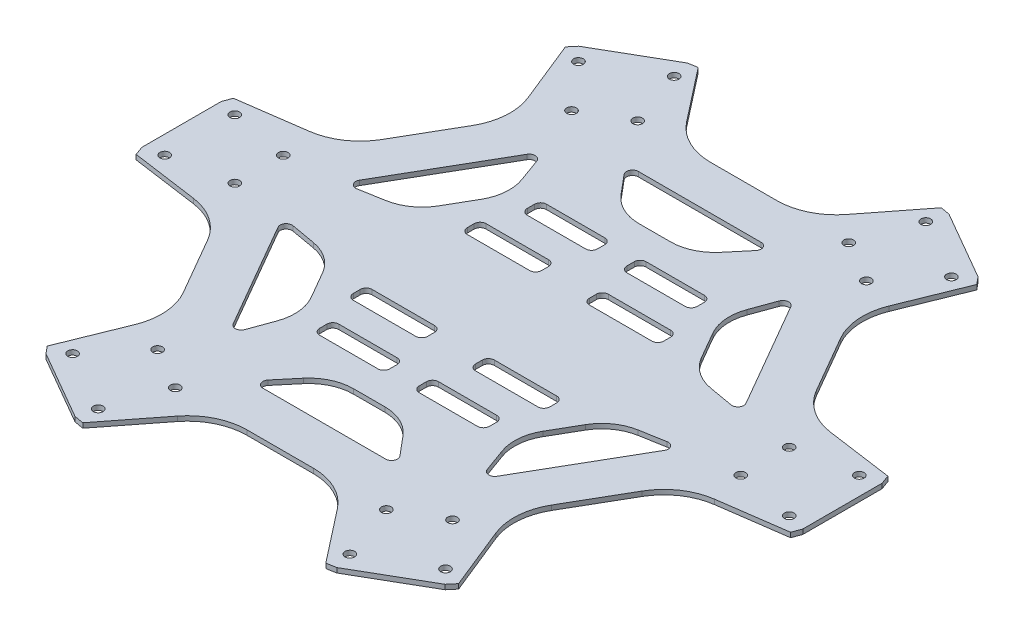
SolidWorks part; units mm, degrees
ref_plane "Front Plane" through (0, 0, 0) normal (0, 0, 1) x (1, 0, 0)
ref_plane "Top Plane" through (0, 0, 0) normal (0, 1, 0) x (1, 0, 0)
ref_plane "Right Plane" through (0, 0, 0) normal (1, 0, 0) x (0, 0, -1)
sketch "Sketch1" plane through (0, 0, 0) normal (0, 1, 0) x (1, 0, 0)
  line L0 (0, 0) -> (-41.6039, 24.02)
  line L1 (-67.498, 38.97) -> (-73.0745, 29.3112)
  line L2 (-87.6116, 19.5059) -> (-110.0668, 16.35)
  line L3 (-110.0668, 16.35) -> (-111.1613, 13.343)
  line L4 (-111.1613, 13.343) -> (-111.1613, 0)
  line L5 (-111.1613, 0) -> (0, 0) construction
  line L6 (-111.1613, 0) -> (-111.1613, -13.343)
  line L7 (-67.498, 38.97) -> (-54.6808, 31.57)
  line L8 (-54.6808, 31.57) -> (-64.9933, 13.7082)
  line L9 (-62.914, 10.7386) -> (-54.614, 12.2021)
  line L10 (-41.6039, 24.02) -> (-44.2284, 19.4742)
  line L11 (-74.306, 16.7755) -> (-53.7192, 4.8897) construction
  line L12 (-65.2613, 17.913) -> (-65.2613, 6.5078) construction
  line L13 (-110.0668, 16.35) -> (-98.8081, 16.35) construction
  line L14 (-62.914, 10.7386) -> (-55.1218, 10.7386) construction
  line L15 (-111.1613, -13.343) -> (-110.0668, -16.35)
  line L16 (-110.0668, -16.35) -> (-87.6116, -19.5059)
  line L17 (-73.0745, -29.3112) -> (-67.498, -38.97)
  line L18 (-67.498, -38.97) -> (-54.6808, -31.57)
  line L19 (-54.6808, -31.57) -> (-64.9933, -13.7082)
  line L20 (-62.914, -10.7386) -> (-54.614, -12.2021)
  line L21 (-44.2284, -19.4742) -> (-41.6039, -24.02)
  line L22 (-41.6039, -24.02) -> (0, 0)
  line L23 (-110.0668, 16.35) -> (-110.0668, -16.35) construction
  line L24 (-87.6116, 19.5059) -> (-87.6116, -19.5059) construction
  line L25 (-105.0363, 11.7806) -> (-105.0363, -11.7806) construction
  line L26 (-85.0763, 8.1431) -> (-85.0763, -8.1431) construction
  line L27 (-108.5636, 12.9259) -> (-103.4648, 13.6425) construction
  line L28 (-106.6613, 12.7082) -> (-106.6613, 10.217) construction
  line L29 (-88.9827, 9.2351) -> (-84.0445, 9.9291) construction
  line L30 (-86.7013, 8.8509) -> (-86.7013, 6.1232) construction
  arc A0 (-73.0745, 29.3112) -> (-87.6116, 19.5059) centre (-90.395, 39.3112) cw
  arc A1 (-64.9933, 13.7082) -> (-62.914, 10.7386) centre (-63.2613, 12.7082) ccw
  arc A2 (-54.614, 12.2021) -> (-44.2284, 19.4742) centre (-57.2187, 26.9742) ccw
  arc A3 (-87.6116, -19.5059) -> (-73.0745, -29.3112) centre (-90.395, -39.3112) cw
  arc A4 (-64.9933, -13.7082) -> (-62.914, -10.7386) centre (-63.2613, -12.7082) cw
  arc A5 (-54.614, -12.2021) -> (-44.2284, -19.4742) centre (-57.2187, -26.9742) cw
  circle A6 centre (-105.0363, 11.7806) radius 1.625
  circle A7 centre (-85.0763, 8.1431) radius 1.625
  circle A8 centre (-105.0363, -11.7806) radius 1.625
  circle A9 centre (-85.0763, -8.1431) radius 1.625
  point P45 (-85.0763, 0)
  point P46 (-105.0363, 0)
  dimension "D5" = 20
  dimension "D7" = 22.625
  dimension "D8" = 2
  dimension "D9" = 15
  dimension "D17" = 3.25
  dimension "D2" = 30
  dimension "D3" = 3.2
  dimension "D4" = 20
  dimension "D6" = 8
  dimension "D10" = 14.8
  dimension "D11" = 15.1
  dimension "D12" = 48.04
  dimension "D13" = 45.9
  dimension "D14" = 10
  dimension "D15" = 16.35
  dimension "D16" = 30
  dimension "D18" = 4.5
  dimension "D19" = 3.6
  dimension "D20" = 24.46
  dimension "D21" = 9.98
extrude "Boss-Extrude1" add sketch "Sketch1" along normal blind 1.6
pattern_circular "CirPattern2" count 6 every 60 about axis through (0, 0, 0) along (0, 1, 0) of "Boss-Extrude1"
sketch "Sketch2" plane through (0, 0, 0) normal (0, 1, 0) x (1, 0, 0)
  line L0 (-26.56, 38.16) -> (-6.96, 38.16)
  line L1 (-4.96, 36.16) -> (-4.96, 33.7)
  line L2 (-6.96, 31.7) -> (-26.56, 31.7)
  line L3 (-28.56, 33.7) -> (-28.56, 36.16)
  line L4 (-31.05, 22.33) -> (-10.05, 22.33)
  line L5 (-8.05, 20.33) -> (-8.05, 18)
  line L6 (-10.05, 16) -> (-31.05, 16)
  line L7 (-33.05, 18) -> (-33.05, 20.33)
  arc A0 (-6.96, 38.16) -> (-4.96, 36.16) centre (-6.96, 36.16) cw
  arc A1 (-4.96, 33.7) -> (-6.96, 31.7) centre (-6.96, 33.7) cw
  arc A2 (-26.56, 31.7) -> (-28.56, 33.7) centre (-26.56, 33.7) cw
  arc A3 (-28.56, 36.16) -> (-26.56, 38.16) centre (-26.56, 36.16) cw
  arc A4 (-10.05, 22.33) -> (-8.05, 20.33) centre (-10.05, 20.33) cw
  arc A5 (-8.05, 18) -> (-10.05, 16) centre (-10.05, 18) cw
  arc A6 (-31.05, 16) -> (-33.05, 18) centre (-31.05, 18) cw
  arc A7 (-33.05, 20.33) -> (-31.05, 22.33) centre (-31.05, 20.33) cw
  dimension "D3" = 2
  dimension "D8" = 2
  dimension "D1" = 23.6
  dimension "D2" = 6.46
  dimension "D4" = 4.96
  dimension "D5" = 31.7
  dimension "D6" = 25
  dimension "D7" = 6.33
  dimension "D9" = 8.05
  dimension "D10" = 16
extrude "Cut-Extrude1" cut sketch "Sketch2" along normal through all
mirror "Mirror5" about plane through (0, 0, 0) normal (0, 0, 1) of "Cut-Extrude1"
mirror "Mirror6" about plane through (0, 0, 0) normal (1, 0, 0) of "Mirror5", "Cut-Extrude1"
